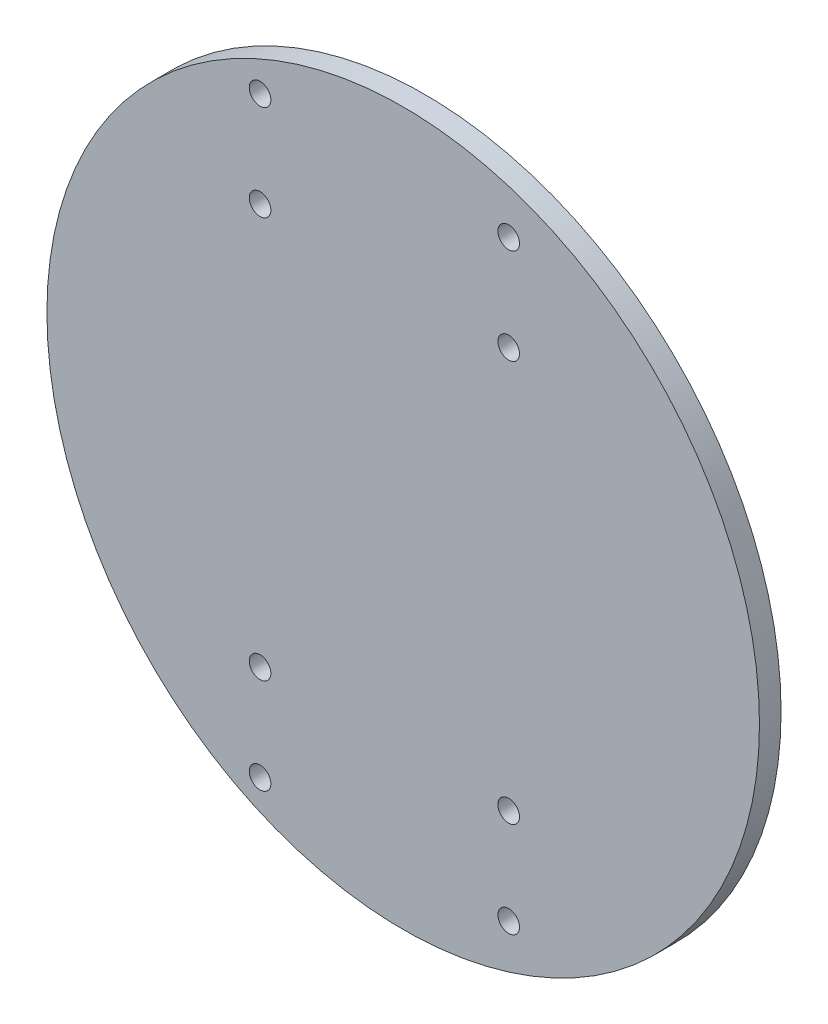
SolidWorks part; units mm, degrees
ref_plane "Alzado" through (0, 0, 0) normal (0, 0, 1) x (1, 0, 0)
ref_plane "Planta" through (0, 0, 0) normal (0, 1, 0) x (1, 0, 0)
ref_plane "Vista lateral" through (0, 0, 0) normal (1, 0, 0) x (0, 0, -1)
sketch "Croquis1" plane through (0, 0, 0) normal (0, 0, 1) x (1, 0, 0)
  circle A0 centre (0, 0) radius 82.42
  dimension "D1" = 164.84
extrude "Saliente-Extruir1" add sketch "Croquis1" along normal blind 5
sketch "Croquis3" plane through (0, 0, 5) normal (0, 0, 1) x (1, 0, 0)
  line L0 (-37.715, 72.96) -> (27.805, 72.96) construction
  line L1 (-37.715, 72.96) -> (27.805, 72.96) construction
  line L2 (27.805, 72.96) -> (27.805, -72.96)
  line L3 (-37.715, 72.96) -> (27.805, 72.96)
  line L4 (-37.715, 72.96) -> (-37.715, -72.96)
  line L5 (-37.715, -72.96) -> (27.805, -72.96)
  line L7 (-37.715, -72.96) -> (-37.715, -68.49) construction
  line L8 (-37.715, -72.96) -> (-33.115, -72.96) construction
  line L9 (-37.715, -68.49) -> (-33.115, -68.49) construction
  line L10 (-33.115, -68.49) -> (-33.115, -72.96) construction
  line L11 (-33.115, -68.49) -> (-33.115, -46.39) construction
  line L12 (-33.115, -46.39) -> (24.405, -46.39) construction
  line L13 (24.405, -46.39) -> (24.405, -68.49) construction
  line L14 (-33.115, -68.49) -> (24.405, -68.49) construction
  line L15 (-4.955, -72.96) -> (-4.955, 72.96) construction
  line L16 (-37.715, 0) -> (27.805, 0) construction
  line L17 (-33.115, 68.49) -> (-37.715, 68.49) construction
  line L18 (-33.115, 68.49) -> (-33.115, 72.96) construction
  circle A0 centre (-33.115, -68.49) radius 2.5
  circle A1 centre (-33.115, -46.39) radius 2.5
  circle A2 centre (0, 0) radius 82.1315
  circle A3 centre (24.405, -46.39) radius 2.5
  circle A4 centre (24.405, -68.49) radius 2.5
  circle A5 centre (24.405, 68.49) radius 2.5
  circle A6 centre (-33.115, 68.49) radius 2.5
  circle A7 centre (24.405, 46.39) radius 2.5
  circle A8 centre (-33.115, 46.39) radius 2.5
  dimension "D5" = 5
  dimension "D7" = 5
  dimension "D9" = 5
  dimension "D11" = 5
  dimension "D1" = 145.92
  dimension "D2" = 65.52
  dimension "D3" = 4.47
  dimension "D4" = 4.6
  dimension "D6" = 22.1
  dimension "D8" = 57.52
  dimension "D10" = 22.1
sketch "Croquis4" plane through (0, 0, 5) normal (0, 0, 1) x (1, 0, 0)
  circle A0 centre (0, 0) radius 82.42
extrude "Cortar-Extruir2" cut sketch "Croquis3" against normal blind 10 contours A6 | A5 | A7 | A8 | A1 | A0 | A3 | A4
